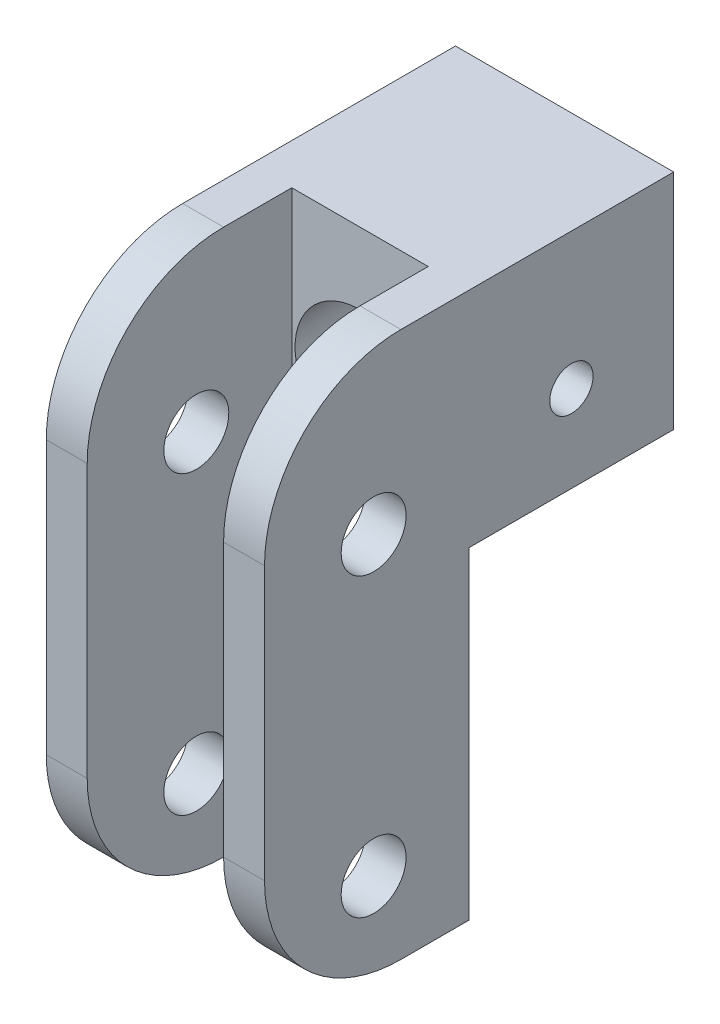
SolidWorks part; units mm, degrees
material "Plain Carbon Steel"
ref_plane "Front" through (0, 0, 0) normal (0, 0, 1) x (1, 0, 0)
ref_plane "Top" through (0, 0, 0) normal (0, 1, 0) x (1, 0, 0)
ref_plane "Right" through (0, 0, 0) normal (1, 0, 0) x (0, 0, -1)
sketch "Sketch1" plane through (0, 0, 0) normal (0, 0, 1) x (1, 0, 0)
  line L0 (0, 0) -> (0, 10) construction
  line L5 (8, -30) -> (8, 10)
  line L6 (8, 10) -> (-8, 10)
  line L7 (-8, 10) -> (-8, -30)
  line L8 (-8, -30) -> (8, -30)
  circle A3 centre (0, 0) radius 2.6 construction
  dimension "D2" = 16
  dimension "D4" = 5.2
  dimension "D6" = 10
  dimension "D7" = 40
extrude "Boss-Extrude1" add sketch "Sketch1" along normal blind 30
hole_wizard "3/8 (0.3750) Dowel Hole1" positions "Sketch2" profile "Sketch3" hole size "3/8" standard "ANSI Inch" end condition through all
sketch "Sketch2" plane through (0, 0, 30) normal (0, 0, 1) x (1, 0, 0)
  point P0 (0, 0)
sketch "Sketch3" plane through (0, 0, 30) normal (1, 0, 0) x (0, -1, 0)
  line L0 (0, 0) -> (0, 30)
  line L1 (0, 30) -> (4.7625, 30)
  line L2 (4.7625, 30) -> (4.7625, 0)
  line L5 (4.7625, 0) -> (0, 0)
  line L11 (0, -6.35) -> (0, 107.95) construction
  dimension "Thru Hole Dia." = 9.525
  dimension "Thru Hole Depth" = 30
hole_wizard "1/8 (0.1250) Dowel Hole1" positions "Sketch4" profile "Sketch5" hole size "1/8" standard "ANSI Inch" end condition through all
sketch "Sketch4" plane through (-8, 0, 0) normal (-1, 0, 0) x (0, 0, 1)
  line L0 (7.5, 10) -> (7.5, 0) construction
  line L2 (30, 10) -> (0, 10) construction
  point P0 (7.5, 0)
  dimension "D1" = 7.5
sketch "Sketch5" plane through (-8, 0, 7.5) normal (0, 1, 0) x (0, 0, 1)
  line L0 (0, 0) -> (0, 16)
  line L1 (0, 16) -> (1.5875, 16)
  line L2 (1.5875, 16) -> (1.5875, 0)
  line L5 (1.5875, 0) -> (0, 0)
  line L11 (0, -6.35) -> (0, 107.95) construction
  dimension "Thru Hole Dia." = 3.175
  dimension "Thru Hole Depth" = 16
sketch "Sketch7" plane through (0, 0, 30) normal (0, 0, 1) x (1, 0, 0)
  line L0 (8, 10) -> (-8, 10) construction
  line L1 (5, 10) -> (-5, 10)
  line L2 (5, 10) -> (5, -30)
  line L3 (5, -30) -> (-5, -30)
  line L4 (-5, 10) -> (-5, -30)
  line L5 (0, 0) -> (0, 10) construction
  line L6 (-8, -30) -> (8, -30) construction
  dimension "D1" = 10
extrude "Cut-Extrude1" cut sketch "Sketch7" against normal offset from surface (15 mm away) 15 up to face at (4.7625, 0, 0)
hole_wizard "3/16 (0.1875) Diameter Hole1" positions "Sketch8" profile "Sketch9" hole size "3/16" standard "ANSI Inch" end condition through all
sketch "Sketch8" plane through (-8, 0, 0) normal (-1, 0, 0) x (0, 0, 1)
  line L0 (22, -23.7) -> (22, -2) construction
  line L1 (22, -2) -> (15, -2) construction
  line L3 (15, 10) -> (15, -30) construction
  line L4 (30, 10) -> (0, 10) construction
  point P0 (22, -2)
  point P2 (22, -23.7)
  point P15 (0, 0)
  dimension "D1" = 7
  dimension "D2" = 21.7
  dimension "D3" = 12
sketch "Sketch9" plane through (-8, -2, 22) normal (0, 1, 0) x (0, 0, 1)
  line L0 (0, 0) -> (0, 16)
  line L1 (0, 16) -> (2.3812, 16)
  line L2 (2.3812, 16) -> (2.3812, 0)
  line L5 (2.3812, 0) -> (0, 0)
  line L11 (0, -6.35) -> (0, 107.95) construction
  dimension "Thru Hole Dia." = 4.7625
  dimension "Thru Hole Depth" = 16
sketch "Sketch10" plane through (0, 0, 0) normal (0, 0, -1) x (-1, 0, 0)
  line L0 (8, 10) -> (8, -30) construction
  line L1 (-8, -30) -> (8, -30)
  line L2 (-8, -30) -> (-8, -6.35)
  line L3 (-8, -6.35) -> (8, -6.35)
  line L4 (8, -30) -> (8, -6.35)
  dimension "D1" = 6.35
extrude "Cut-Extrude2" cut sketch "Sketch10" against normal up to surface (15 mm away) up to face at (0, -10, 15)
fillet "Fillet1" radius 10 4 edges at (-6.5, -30, 30) (6.5, -30, 30) (-6.5, 10, 30) (6.5, 10, 30)
